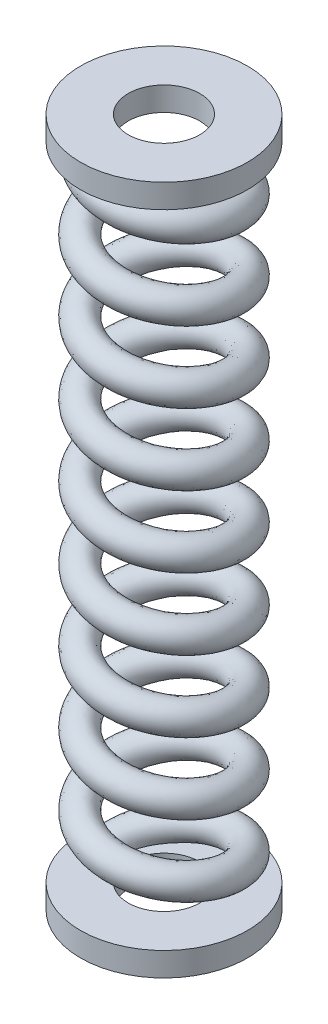
SolidWorks part; units mm, degrees
ref_plane "Front Plane" through (0, 0, 0) normal (0, 0, 1) x (1, 0, 0)
ref_plane "Top Plane" through (0, 0, 0) normal (0, 1, 0) x (1, 0, 0)
ref_plane "Right Plane" through (0, 0, 0) normal (1, 0, 0) x (0, 0, -1)
sketch "Sketch1" plane through (0, 0, 0) normal (0, 1, 0) x (1, 0, 0)
  circle A0 centre (0, 0) radius 5
  dimension "D1" = 10
curve "Spiral" pitch 5.9778 height 53.8 turns 9
sweep "Body" add path "Spiral" circular profile diameter 2.5 parameters "D3"=2.5
sketch "Axis" plane through (0, 0, 0) normal (0, 0, 1) x (1, 0, 0)
  line L0 (0, 0) -> (0, 53.8) construction
  dimension "D1" = 53.8
sketch "Sketch17" plane through (0, 0, 0) normal (0, 1, 0) x (1, 0, 0)
  circle A0 centre (0, 0) radius 7
  dimension "D1" = 14
extrude "Bottom" add sketch "Sketch17" against normal blind 2
ref_plane "Top_Plane" through (0, 53.8, 0) normal (0, 1, 0) x (1, 0, 0)
sketch "Sketch24" plane through (0, 53.8, 0) normal (0, 1, 0) x (1, 0, 0)
  circle A0 centre (0, 0) radius 7
  dimension "D1" = 14
extrude "Top" add sketch "Sketch24" along normal blind 2
sketch "Sketch25" plane through (0, -2, 0) normal (0, -1, 0) x (1, 0, 0)
  circle A0 centre (0, 0) radius 3
  dimension "D1" = 6
extrude "Axis_Hole" cut sketch "Sketch25" against normal through all
